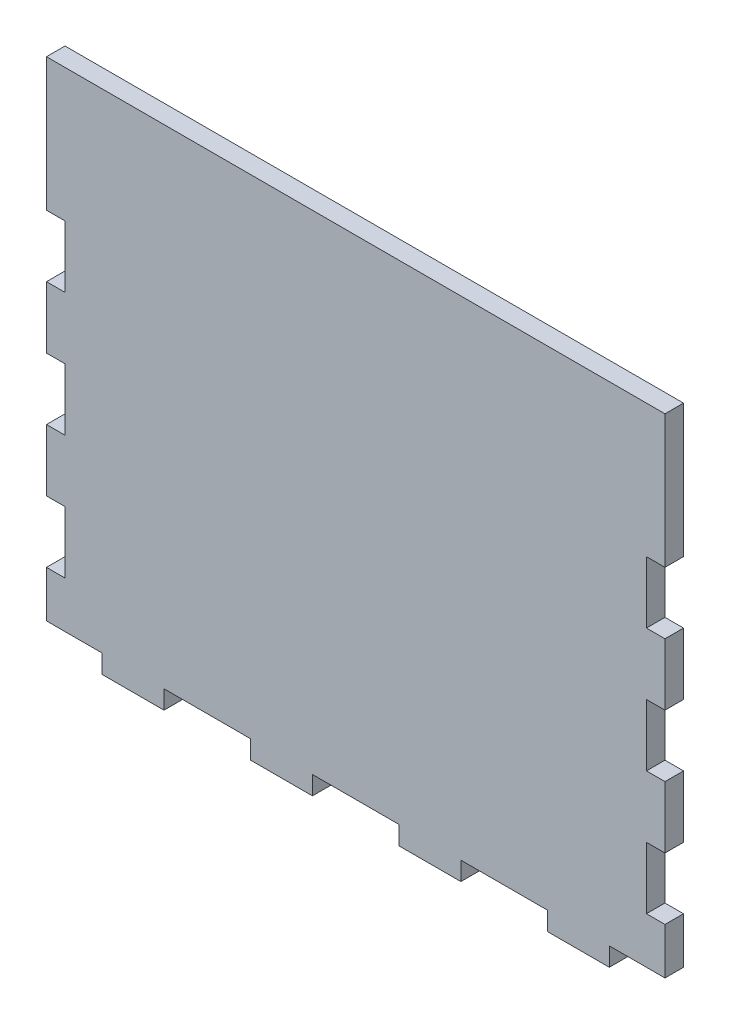
SolidWorks part; units mm, degrees
ref_plane "前基準面" through (0, 0, 0) normal (0, 0, 1) x (1, 0, 0)
ref_plane "上基準面" through (0, 0, 0) normal (0, 1, 0) x (1, 0, 0)
ref_plane "右基準面" through (0, 0, 0) normal (1, 0, 0) x (0, 0, -1)
sketch "草圖1" plane through (0, 0, 0) normal (0, 0, 1) x (1, 0, 0)
  line L0 (-11.9193, -41.7083) -> (-11.9193, -60.4731) construction
  line L1 (-61.9193, 23.7181) -> (-52.9193, 23.7181)
  line L2 (-61.9193, 23.7181) -> (-61.9193, 16.2181)
  line L3 (-61.9193, -41.2819) -> (-52.9193, -41.2819)
  line L4 (38.0807, 23.7181) -> (38.0807, 16.2181)
  line L5 (19.0807, -44.2819) -> (29.0807, -44.2819)
  line L7 (-28.9193, -41.2819) -> (-28.9193, -44.2819)
  line L8 (-28.9193, -44.2819) -> (-18.9193, -44.2819)
  line L9 (-18.9193, -41.2819) -> (-18.9193, -44.2819)
  line L11 (-42.9193, -41.2819) -> (-42.9193, -44.2819)
  line L12 (-42.9193, -44.2819) -> (-52.9193, -44.2819)
  line L13 (-52.9193, -41.2819) -> (-52.9193, -44.2819)
  line L14 (29.0807, -41.2819) -> (29.0807, -44.2819)
  line L16 (19.0807, -41.2819) -> (19.0807, -44.2819)
  line L17 (5.0807, -44.2819) -> (-4.9193, -44.2819)
  line L18 (-4.9193, -41.2819) -> (-4.9193, -44.2819)
  line L20 (5.0807, -41.2819) -> (5.0807, -44.2819)
  line L21 (-61.9193, -8.7819) -> (38.0807, -8.7819) construction
  line L23 (19.0807, 23.7181) -> (19.0807, 26.7181)
  line L25 (29.0807, 23.7181) -> (29.0807, 26.7181)
  line L26 (19.0807, 26.7181) -> (29.0807, 26.7181)
  line L27 (5.0807, 23.7181) -> (5.0807, 26.7181)
  line L29 (-4.9193, 23.7181) -> (-4.9193, 26.7181)
  line L30 (5.0807, 26.7181) -> (-4.9193, 26.7181)
  line L31 (-28.9193, 26.7181) -> (-18.9193, 26.7181)
  line L32 (-18.9193, 23.7181) -> (-18.9193, 26.7181)
  line L34 (-28.9193, 23.7181) -> (-28.9193, 26.7181)
  line L35 (-42.9193, 26.7181) -> (-52.9193, 26.7181)
  line L36 (-52.9193, 23.7181) -> (-52.9193, 26.7181)
  line L38 (-42.9193, 23.7181) -> (-42.9193, 26.7181)
  line L39 (-42.9193, 23.7181) -> (-28.9193, 23.7181)
  line L40 (-18.9193, 23.7181) -> (-4.9193, 23.7181)
  line L41 (5.0807, 23.7181) -> (19.0807, 23.7181)
  line L42 (29.0807, 23.7181) -> (38.0807, 23.7181)
  line L43 (29.0807, -41.2819) -> (38.0807, -41.2819)
  line L44 (5.0807, -41.2819) -> (19.0807, -41.2819)
  line L45 (-18.9193, -41.2819) -> (-4.9193, -41.2819)
  line L46 (-42.9193, -41.2819) -> (-28.9193, -41.2819)
  line L47 (-61.9193, -33.7819) -> (-58.9193, -33.7819)
  line L48 (-61.9193, -3.7819) -> (-58.9193, -3.7819)
  line L50 (-61.9193, -13.7819) -> (-58.9193, -13.7819)
  line L51 (-58.9193, -3.7819) -> (-58.9193, -13.7819)
  line L52 (-61.9193, 6.2181) -> (-58.9193, 6.2181)
  line L54 (-61.9193, 16.2181) -> (-58.9193, 16.2181)
  line L55 (-58.9193, 6.2181) -> (-58.9193, 16.2181)
  line L56 (-58.9193, -23.7819) -> (-58.9193, -33.7819)
  line L57 (-61.9193, -23.7819) -> (-58.9193, -23.7819)
  line L60 (38.0807, -23.7819) -> (35.0807, -23.7819)
  line L61 (35.0807, -23.7819) -> (35.0807, -33.7819)
  line L62 (38.0807, -33.7819) -> (35.0807, -33.7819)
  line L63 (38.0807, -13.7819) -> (35.0807, -13.7819)
  line L64 (35.0807, -3.7819) -> (35.0807, -13.7819)
  line L65 (38.0807, -3.7819) -> (35.0807, -3.7819)
  line L67 (38.0807, 16.2181) -> (35.0807, 16.2181)
  line L68 (35.0807, 6.2181) -> (35.0807, 16.2181)
  line L69 (38.0807, 6.2181) -> (35.0807, 6.2181)
  line L71 (-61.9193, -33.7819) -> (-61.9193, -41.2819)
  line L72 (-61.9193, -13.7819) -> (-61.9193, -23.7819)
  line L73 (-61.9193, 6.2181) -> (-61.9193, -3.7819)
  line L74 (38.0807, 6.2181) -> (38.0807, -3.7819)
  line L75 (38.0807, -13.7819) -> (38.0807, -23.7819)
  line L76 (38.0807, -33.7819) -> (38.0807, -41.2819)
  line L77 (-61.9193, 23.7181) -> (38.0807, 23.7181)
  line L78 (-61.9193, 23.7181) -> (-61.9193, 37.7181)
  line L79 (-61.9193, 37.7181) -> (38.0807, 37.7181)
  line L80 (38.0807, 23.7181) -> (38.0807, 37.7181)
  point P46 (-58.9193, -8.7819)
  dimension "D1" = 100
  dimension "D2" = 65
  dimension "D3" = 3
  dimension "D4" = 10
  dimension "D5" = 7
  dimension "D6" = 3
  dimension "D7" = 10
  dimension "D8" = 14
  dimension "D9" = 3
  dimension "D10" = 10
  dimension "D11" = 9
  dimension "D12" = 3
  dimension "D13" = 10
  dimension "D14" = 10
  dimension "D15" = 14
extrude "填料-伸長1" add sketch "草圖1" along normal blind 3 contours L42 L80 L79 L78 L1 L36 L35 L38 L39 L34 L31 L32 L40 L29 L30 L27 L41 L23 L26 L25 | L36 L77 L38 L35 | L34 L77 L32 L31 | L29 L77 L27 L30 | L23 L77 L25 L26 | L77 L1 L2 L54 L55 L52 L73 L48 L51 L50 L72 L57 L56 L47 L71 L3 L13 L12 L11 L46 L7 L8 L9 L45 L18 L17 L20 L44 L16 L5 L14 L43 L76 L62 L61 L60 L75 L63 L64 L65 L74 L69 L68 L67 L4 L42 L41 L40
